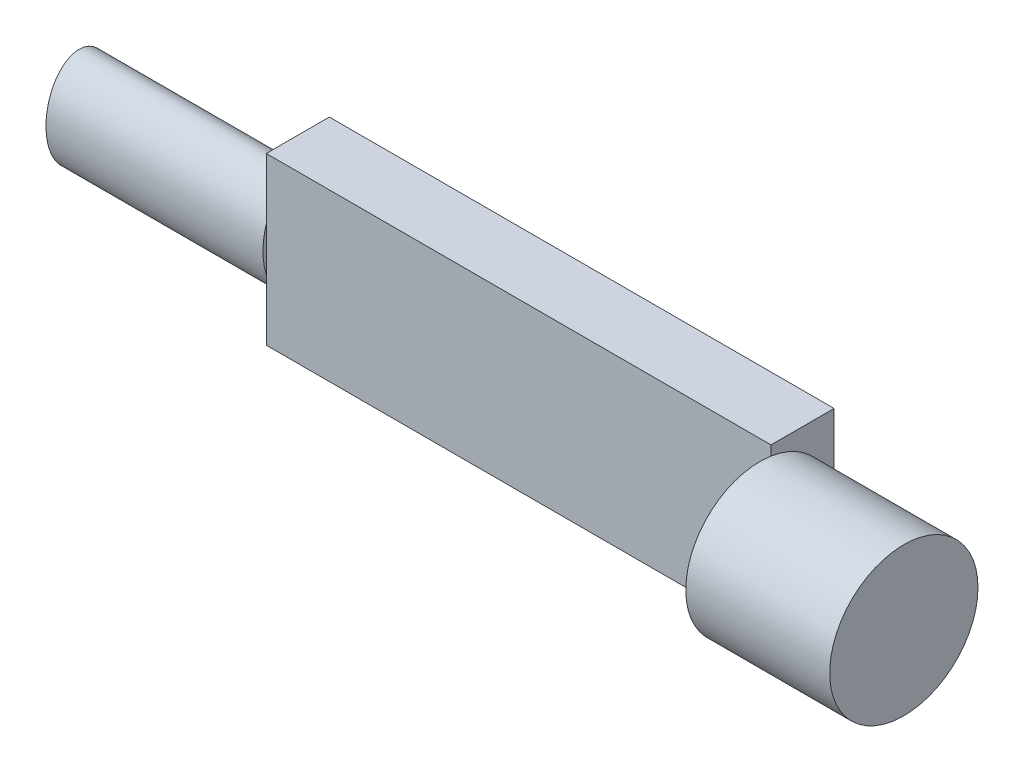
SolidWorks part; units mm, degrees
ref_plane "Front Plane" through (0, 0, 0) normal (0, 0, 1) x (1, 0, 0)
ref_plane "Top Plane" through (0, 0, 0) normal (0, 1, 0) x (1, 0, 0)
ref_plane "Right Plane" through (0, 0, 0) normal (1, 0, 0) x (0, 0, -1)
sketch "Sketch2" plane through (0, 0, 0) normal (0, 0, 1) x (1, 0, 0)
  line L1 (0, 0) -> (22.8, 0)
  line L2 (0, 0) -> (0, 7.5)
  line L3 (0, 7.5) -> (22.8, 7.5)
  line L4 (22.8, 0) -> (22.8, 7.5)
  line L5 (0, 0) -> (22.8, 7.5) construction
  line L6 (0, 7.5) -> (22.8, 0) construction
  point P4 (11.4, 3.75)
  dimension "D1" = 22.8
  dimension "D2" = 7.5
extrude "Boss-Extrude1" add sketch "Sketch2" along normal blind 2.85
sketch "Sketch3" plane through (22.8, 0, 0) normal (1, 0, 0) x (0, 0, -1)
  line L0 (-2.85, 3.75) -> (0, 3.75) construction
  line L1 (-2.85, 0) -> (-2.85, 7.5) construction
  line L2 (0, 0) -> (0, 7.5) construction
  circle A0 centre (-3.35, 3.75) radius 3.35
  point P6 (0, 0)
  point P7 (0, 0)
  dimension "D1" = 6.7
extrude "Boss-Extrude2" add sketch "Sketch3" along normal blind 6.5
sketch "Sketch4" plane through (0, 0, 0) normal (-1, 0, 0) x (0, 0, 1)
  line L1 (0, 7.5) -> (0, 0) construction
  line L2 (1.5, 6) -> (1.5, 1.5) construction
  ellipse E0 centre (1.5, 3.75) end of major axis (1.5, 6) minor radius 1.5
  dimension "D1" = 4.5
  dimension "D2" = 3
extrude "Boss-Extrude3" add sketch "Sketch4" along normal blind 9.8
